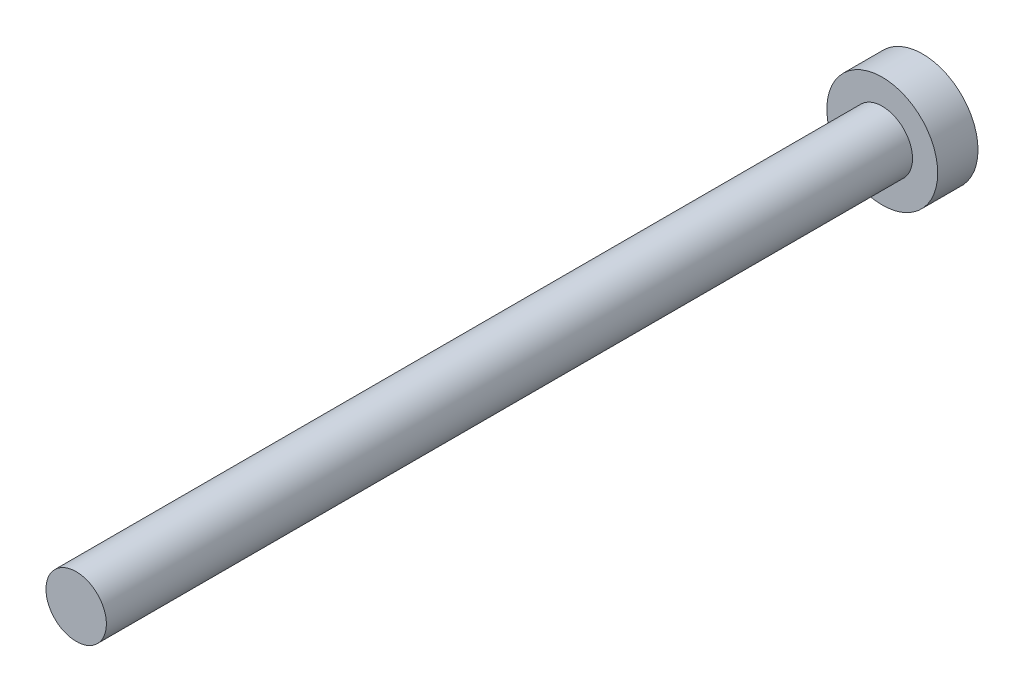
SolidWorks part; units mm, degrees
ref_plane "前视基准面" through (0, 0, 0) normal (0, 0, 1) x (1, 0, 0)
ref_plane "上视基准面" through (0, 0, 0) normal (0, 1, 0) x (1, 0, 0)
ref_plane "右视基准面" through (0, 0, 0) normal (1, 0, 0) x (0, 0, -1)
other "Configuration Table"
sketch "草图1" plane through (0, 0, 0) normal (0, 0, 1) x (1, 0, 0)
  circle A0 centre (0, 0) radius 1.5
extrude "M3x40螺杆简化" add sketch "草图1" along normal blind 40
sketch "草图2" plane through (0, 0, 0) normal (0, 0, 1) x (1, 0, 0)
  circle A0 centre (0, 0) radius 2.75
extrude "M3螺钉头简化" add sketch "草图2" along normal blind 2 from offset 2
